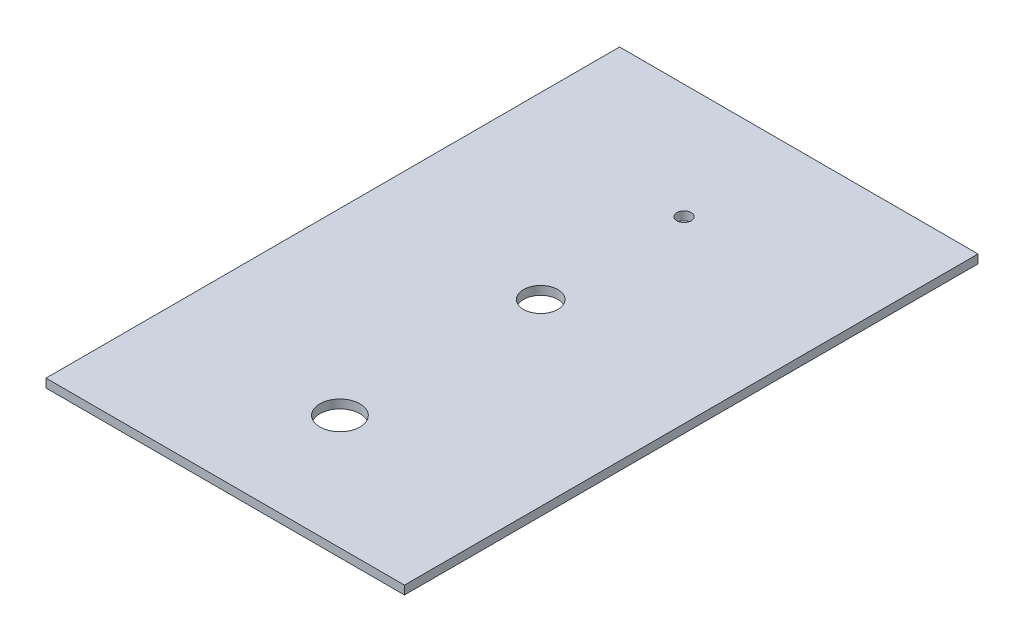
SolidWorks part; units mm, degrees
ref_plane "Front Plane" through (0, 0, 0) normal (0, 0, 1) x (1, 0, 0)
ref_plane "Top Plane" through (0, 0, 0) normal (0, 1, 0) x (1, 0, 0)
ref_plane "Right Plane" through (0, 0, 0) normal (1, 0, 0) x (0, 0, -1)
sketch "Sketch1" plane through (0, 0, 0) normal (0, 1, 0) x (1, 0, 0)
  line L1 (-62.5, -100) -> (62.5, -100)
  line L2 (-62.5, -100) -> (-62.5, 100)
  line L3 (-62.5, 100) -> (62.5, 100)
  line L4 (62.5, -100) -> (62.5, 100)
  line L5 (-62.5, -100) -> (62.5, 100) construction
  line L6 (-62.5, 100) -> (62.5, -100) construction
  point P0 (0, 0)
  dimension "D1" = 125
  dimension "D2" = 200
extrude "Boss-Extrude1" add sketch "Sketch1" along normal blind 3
sketch "Sketch2" plane through (0, 3, 0) normal (0, 1, 0) x (1, 0, 0)
  line L0 (0, 100) -> (0, -100) construction
  line L1 (62.5, 100) -> (-62.5, 100) construction
  line L2 (-62.5, -100) -> (62.5, -100) construction
  circle A0 centre (0, 60) radius 2.5
  circle A1 centre (0, -60) radius 7
  circle A2 centre (0, 10) radius 6
  dimension "D1" = 5
  dimension "D2" = 12
  dimension "D3" = 14
  dimension "D4" = 40
  dimension "D5" = 90
  dimension "D6" = 160
extrude "Cut-Extrude1" cut sketch "Sketch2" along direction (0, -1, 0) on the side against the normal up to next (3 mm away)
